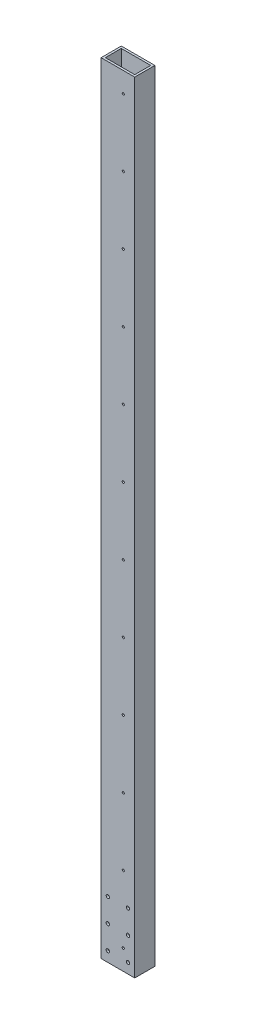
SolidWorks part; units mm, degrees
material "6061-T6 (SS)"
ref_plane "Front Plane" through (0, 0, 0) normal (0, 0, 1) x (1, 0, 0)
ref_plane "Top Plane" through (0, 0, 0) normal (0, 1, 0) x (1, 0, 0)
ref_plane "Right Plane" through (0, 0, 0) normal (1, 0, 0) x (0, 0, -1)
sketch "Sketch1" plane through (0, 0, 0) normal (0, 1, 0) x (1, 0, 0)
  line L1 (-77.9743, -5.5718) -> (-14.4743, -5.5718)
  line L2 (-77.9743, -5.5718) -> (-77.9743, 32.5282)
  line L3 (-77.9743, 32.5282) -> (-14.4743, 32.5282)
  line L4 (-14.4743, -5.5718) -> (-14.4743, 32.5282)
  dimension "D1" = 63.5
  dimension "D2" = 38.1
extrude "Extrude-Thin1" add sketch "Sketch1" along normal blind 1473.2 thin thin type one direction reverse wall 3.9624
sketch "Sketch2" plane through (0, 0, 5.5718) normal (0, 0, 1) x (1, 0, 0)
  circle A0 centre (-36.0643, 38.1) radius 10.1396
  circle A1 centre (-36.0643, 165.1) radius 10.1396
  circle A2 centre (-36.0643, 292.1) radius 10.1396
  circle A3 centre (-36.0643, 419.1) radius 10.1396
  circle A4 centre (-36.0643, 546.1) radius 10.1396
  circle A5 centre (-36.0643, 673.1) radius 10.1396
  circle A6 centre (-36.0643, 800.1) radius 10.1396
  circle A7 centre (-36.0643, 927.1) radius 10.1396
  circle A8 centre (-36.0643, 1054.1) radius 10.1396
  circle A9 centre (-36.0643, 1181.1) radius 10.1396
  circle A10 centre (-36.0643, 1308.1) radius 10.1396
  circle A11 centre (-36.0643, 1435.1) radius 10.1396
  dimension "D1" = 21.59
  dimension "D2" = 38.1
hole_wizard "#10-32 Tapped Hole1" positions "Sketch6" profile "Sketch5" tap size "#10-32" standard "ANSI Inch"
sketch "Sketch6" plane through (0, 0, 5.5718) normal (0, 0, 1) x (1, 0, 0)
  point P0 (-36.0643, 38.1)
  point P3 (-36.0643, 165.1)
  point P6 (-36.0643, 292.1)
  point P9 (-36.0643, 419.1)
  point P12 (-36.0643, 546.1)
  point P15 (-36.0643, 673.1)
  point P18 (-36.0643, 800.1)
  point P21 (-36.0643, 927.1)
  point P24 (-36.0643, 1054.1)
  point P27 (-36.0643, 1181.1)
  point P30 (-36.0643, 1308.1)
  point P33 (-36.0643, 1435.1)
sketch "Sketch5" plane through (-36.0643, 38.1, 5.5718) normal (1, 0, 0) x (0, -1, 0)
  line L0 (0, 0) -> (0, 21.3809)
  line L1 (0, 21.3809) -> (2.0193, 20.1676)
  line L2 (2.0193, 20.1676) -> (2.0193, 0)
  line L5 (2.0193, 0) -> (0, 0)
  line L10 (0, 21.3809) -> (-2.0193, 20.1676) construction
  line L11 (0, -6.35) -> (0, 107.95) construction
  dimension "Tap Drill Dia." = 4.0386
  dimension "Tap Drill Depth" = 20.1676
  dimension "Drill Angle" = 118
cosmetic thread "Hole Thread1" parameters "D1"=3.9624, "D2"=4.826
cosmetic thread "Hole Thread2" parameters "D1"=3.9624, "D2"=4.826
cosmetic thread "Hole Thread3" parameters "D1"=3.9624, "D2"=4.826
cosmetic thread "Hole Thread4" parameters "D1"=3.9624, "D2"=4.826
cosmetic thread "Hole Thread5" parameters "D1"=3.9624, "D2"=4.826
cosmetic thread "Hole Thread6" parameters "D1"=3.9624, "D2"=4.826
cosmetic thread "Hole Thread7" parameters "D1"=3.9624, "D2"=4.826
cosmetic thread "Hole Thread8" parameters "D1"=3.9624, "D2"=4.826
cosmetic thread "Hole Thread9" parameters "D1"=3.9624, "D2"=4.826
cosmetic thread "Hole Thread10" parameters "D1"=3.9624, "D2"=4.826
cosmetic thread "Hole Thread11" parameters "D1"=3.9624, "D2"=4.826
cosmetic thread "Hole Thread12" parameters "D1"=3.9624, "D2"=4.826
hole_wizard "1/4 (0.25) Diameter Hole1" positions "Sketch7" profile "Sketch8" hole size "1/4" standard "ANSI Inch"
sketch "Sketch7" plane through (-297.2606, -585.3001, -36.0842) normal (0, 0, -1) x (-1, 0, 0)
  point P0 (-270.0863, 693.2501)
  point P3 (-231.9863, 693.2501)
  point P6 (-270.0863, 648.8001)
  point P9 (-231.9863, 648.8001)
  point P12 (-270.0863, 604.3501)
  point P15 (-231.9863, 604.3501)
sketch "Sketch8" plane through (-27.1743, 107.95, -36.0842) normal (0, 1, 0) x (-1, 0, 0)
  line L0 (0, 0) -> (0, 103.5077)
  line L1 (0, 103.5077) -> (3.175, 101.6)
  line L2 (3.175, 101.6) -> (3.175, 0)
  line L3 (3.175, 0) -> (0, 0)
  line L4 (0, 103.5077) -> (-3.175, 101.6) construction
  line L5 (0, -6.35) -> (0, 107.95) construction
  dimension "Hole Dia." = 6.35
  dimension "Hole Depth" = 101.6
  dimension "Drill Angle" = 118
